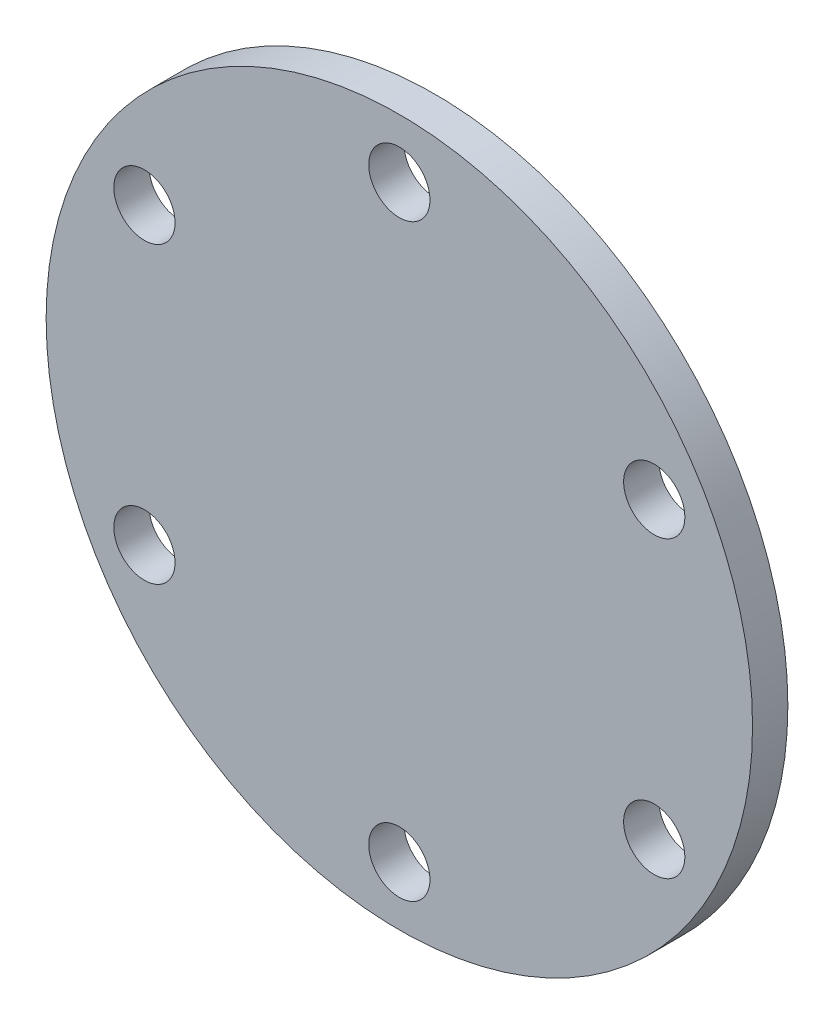
SolidWorks part; units mm, degrees
ref_plane "Alzado" through (0, 0, 0) normal (0, 0, 1) x (1, 0, 0)
ref_plane "Planta" through (0, 0, 0) normal (0, 1, 0) x (1, 0, 0)
ref_plane "Vista lateral" through (0, 0, 0) normal (1, 0, 0) x (0, 0, -1)
sketch "Sketch1" plane through (0, 0, 0) normal (0, 0, 1) x (1, 0, 0)
  circle A0 centre (0, 0) radius 25 construction
  circle A1 centre (0, 0) radius 30
  circle A2 centre (0, 25) radius 2.6
  circle A3 centre (21.6506, 12.5) radius 2.6
  circle A4 centre (21.6506, -12.5) radius 2.6
  circle A5 centre (0, -25) radius 2.6
  circle A6 centre (-21.6506, -12.5) radius 2.6
  circle A7 centre (-21.6506, 12.5) radius 2.6
  point P19 (0, 0)
  dimension "D1" = 60
  dimension "D2" = 50
  dimension "D3" = 5.2
  dimension "D4" = 6
extrude "Boss-Extrude1" add sketch "Sketch1" along normal blind 3
